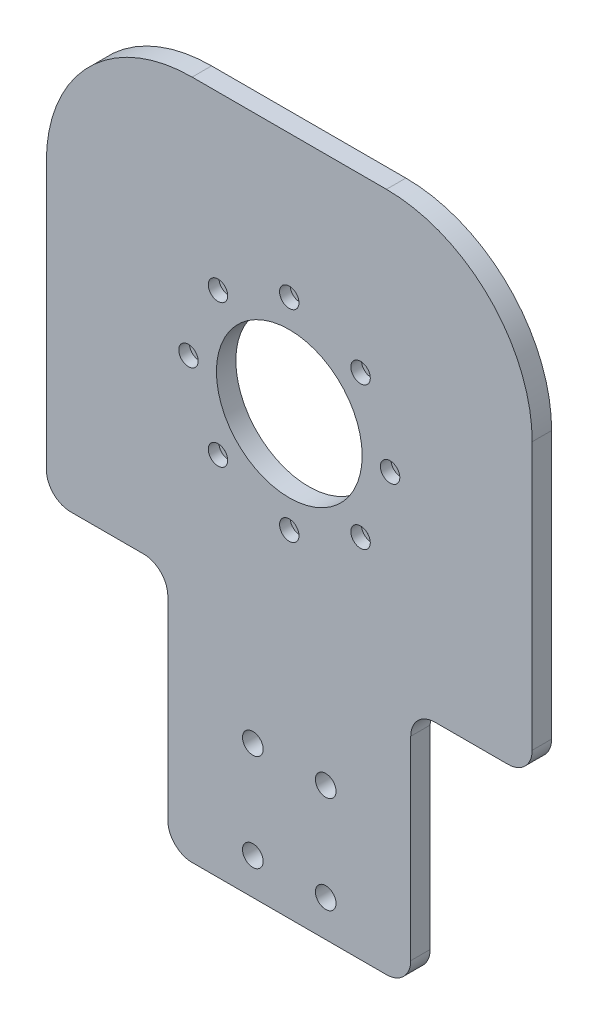
SolidWorks part; units mm, degrees
ref_plane "前视基准面" through (0, 0, 0) normal (0, 0, 1) x (1, 0, 0)
ref_plane "上视基准面" through (0, 0, 0) normal (0, 1, 0) x (1, 0, 0)
ref_plane "右视基准面" through (0, 0, 0) normal (1, 0, 0) x (0, 0, -1)
other "Configuration Table"
sketch "草图1" plane through (0, 0, 0) normal (0, 0, 1) x (1, 0, 0)
  line L0 (0, 0) -> (0, 498.031) construction
  line L1 (100, 0) -> (-100, 0)
  line L2 (-100, 0) -> (-100, 400)
  line L3 (-100, 400) -> (100, 400)
  line L4 (100, 0) -> (100, 400)
  point P7 (0, 400)
  dimension "D1" = 400
  dimension "D2" = 100
extrude "凸台-拉伸1" add sketch "草图1" along normal blind 8
sketch "草图2" plane through (0, 0, 0) normal (0, 0, -1) x (-1, 0, 0)
  line L0 (100, 0) -> (-100, 0) construction
  circle A0 centre (0, 300) radius 30
  circle A1 centre (0, 300) radius 81.25 construction
  dimension "D1" = 60
  dimension "D3" = 162.5
  dimension "D2" = 300
extrude "切除-拉伸1" cut sketch "草图2" against normal blind 10
sketch "草图3" plane through (0, 0, 0) normal (0, 0, -1) x (-1, 0, 0)
  line L0 (0, 300) -> (0, 473.0171) construction
  circle A0 centre (0, 300) radius 41.5 construction
  circle A1 centre (0, 341.5) radius 2.25
  circle A2 centre (29.3449, 329.3449) radius 2.25
  circle A3 centre (41.5, 300) radius 2.25
  circle A4 centre (29.3449, 270.6551) radius 2.25
  circle A5 centre (0, 258.5) radius 2.25
  circle A6 centre (-29.3449, 270.6551) radius 2.25
  circle A7 centre (-41.5, 300) radius 2.25
  circle A8 centre (-29.3449, 329.3449) radius 2.25
  point P23 (0, 300)
  dimension "D1" = 83
  dimension "D2" = 4.5
  dimension "D3" = 8
extrude "切除-拉伸2" cut sketch "草图3" against normal blind 10
sketch "草图4" plane through (0, 0, 8) normal (0, 0, 1) x (1, 0, 0)
  circle A0 centre (29.3449, 329.3449) radius 4
  circle A1 centre (41.5, 300) radius 4
  circle A2 centre (29.3449, 270.6551) radius 4
  circle A3 centre (0, 258.5) radius 4
  circle A4 centre (-29.3449, 270.6551) radius 4
  circle A5 centre (-41.5, 300) radius 4
  circle A6 centre (-29.3449, 329.3449) radius 4
  circle A7 centre (0, 341.5) radius 4
  point P19 (0, 300)
  dimension "D1" = 8
  dimension "D2" = 8
extrude "切除-拉伸3" cut sketch "草图4" against normal blind 4.4
fillet "圆角1" radius 60 2 edges at (-100, 400, 4) (100, 400, 4)
sketch "草图5" plane through (0, 0, 0) normal (0, 0, -1) x (-1, 0, 0)
  line L0 (0, 0) -> (0, 210.4688) construction
  line L1 (-31.1787, 84) -> (29.3504, 84) construction
  line L2 (-31.1787, 194) -> (29.3504, 194) construction
  line L5 (78.9299, 160) -> (16.8198, 160) construction
  circle A0 centre (-15, 25) radius 4.25
  circle A1 centre (15, 25) radius 4.25
  circle A2 centre (-15, 65) radius 4.25
  circle A3 centre (15, 65) radius 4.25
  circle A4 centre (-15, 175) radius 4.25
  circle A5 centre (-15, 135) radius 4.25
  circle A6 centre (15, 135) radius 4.25
  circle A7 centre (15, 175) radius 4.25
  dimension "D1" = 8.5
  dimension "D2" = 25
  dimension "D3" = 30
  dimension "D4" = 70
  dimension "D6" = 40
  dimension "D7" = 19
  dimension "D8" = 2
extrude "切除-拉伸4" cut sketch "草图5" against normal blind 10
sketch "草图6" plane through (0, 0, 8) normal (0, 0, 1) x (1, 0, 0)
  line L0 (0, 0) -> (0, 496.7926) construction
  line L1 (-50, 0) -> (-50, 220)
  line L2 (100, 0) -> (50, 0)
  line L3 (100, 0) -> (100, 220)
  line L4 (100, 220) -> (50, 220)
  line L5 (50, 0) -> (50, 220)
  line L6 (-100, 220) -> (-50, 220)
  line L7 (-100, 0) -> (-100, 220)
  line L8 (-100, 0) -> (-50, 0)
  dimension "D1" = 50
  dimension "D2" = 220
extrude "切除-拉伸5" cut sketch "草图6" against normal blind 10
fillet "圆角2" radius 10 4 edges at (-100, 220, 4) (-50, 220, 4) (50, 220, 4) (100, 220, 4)
sketch "草图7" plane through (0, 0, 0) normal (0, 0, -1) x (-1, 0, 0)
  line L0 (-50, 210) -> (-50, 0) construction
  line L1 (50, 0) -> (-50, 0)
  line L2 (50, 0) -> (50, 120)
  line L3 (50, 120) -> (-50, 120)
  line L4 (-50, 0) -> (-50, 120)
  dimension "D1" = 120
extrude "切除-拉伸6" cut sketch "草图7" against normal blind 84
fillet "圆角3" radius 10 2 edges at (50, 120, 4) (-50, 120, 4)
